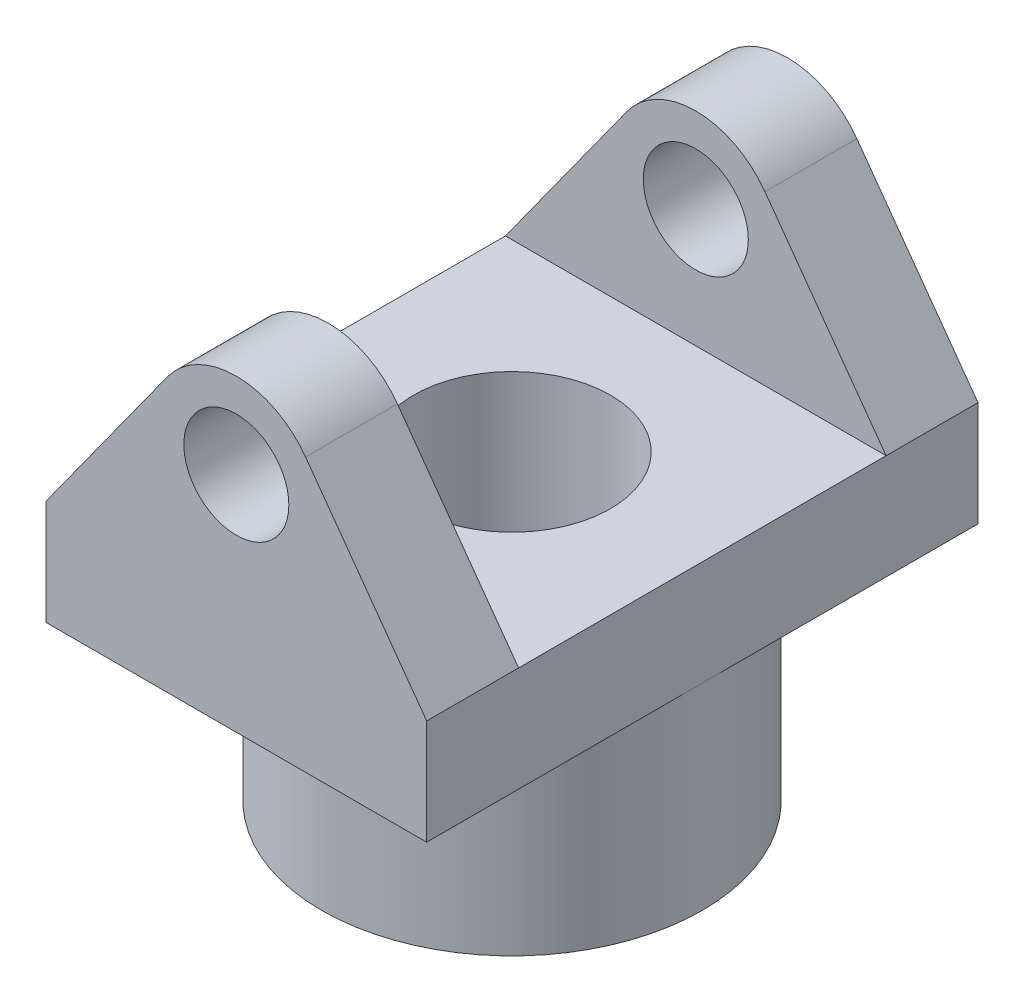
SolidWorks part; units mm, degrees
ref_plane "Front Plane" through (0, 0, 0) normal (1, 0, 0) x (0, 1, 0)
ref_plane "Top Plane" through (0, 0, 0) normal (0, 0, 1) x (0, 1, 0)
ref_plane "Right Plane" through (0, 0, 0) normal (0, 1, 0) x (-1, 0, 0)
sketch "Sketch1" plane through (0, 0, 0) normal (0, 1, 0) x (-1, 0, 0)
  circle A0 centre (0, 0) radius 29
  dimension "D1" = 58
extrude "Boss-Extrude1" add sketch "Sketch1" along normal blind 30
sketch "Sketch3" plane through (0, 30, 0) normal (0, 1, 0) x (-1, 0, 0)
  line L0 (-29, 42) -> (29, 42)
  line L1 (29, 42) -> (29, -42)
  line L2 (29, -42) -> (-29, -42)
  line L3 (-29, -42) -> (-29, 42)
  line L5 (0, 0) -> (0, 50000) construction
  line L6 (0, 0) -> (50000, 0) construction
  dimension "D1" = 84
  dimension "D4" = 58
extrude "Boss-Extrude2" add sketch "Sketch3" along normal blind 16
sketch "Sketch4" plane through (0, 0, 42) normal (0, 0, 1) x (1, 0, 0)
  line L0 (-29, 30) -> (-29, 46)
  line L1 (-29, 46) -> (-10.5459, 71.6016)
  line L2 (10.5459, 71.6016) -> (29, 46)
  line L3 (29, 46) -> (29, 30)
  line L4 (29, 30) -> (-29, 30)
  arc A0 (-10.5459, 71.6016) -> (10.5459, 71.6016) centre (0, 64) cw
  circle A1 centre (0, 64) radius 8
  dimension "D2" = 13
  dimension "D3" = 16
  dimension "D1" = 34
extrude "q" add sketch "Sketch4" against normal blind 14
mirror "Mirror1" about plane through (0, 0, 0) normal (0, 0, 1) of "q"
sketch "Sketch5" plane through (0, 0, 0) normal (0, -1, 0) x (1, 0, 0)
  line L1 (-4, 17.4568) -> (4, 17.4568)
  line L2 (-4, 17.4568) -> (-4, 14.4568)
  line L4 (4, 17.4568) -> (4, 14.4568)
  arc A0 (-4, 14.4568) -> (4, 14.4568) centre (0, 0) ccw
  point P7 (0, 17.4568)
  point P8 (0, 15)
  dimension "D1" = 30
  dimension "D2" = 3
  dimension "D3" = 8
extrude "Cut-Extrude1" cut sketch "Sketch5" against normal through all
